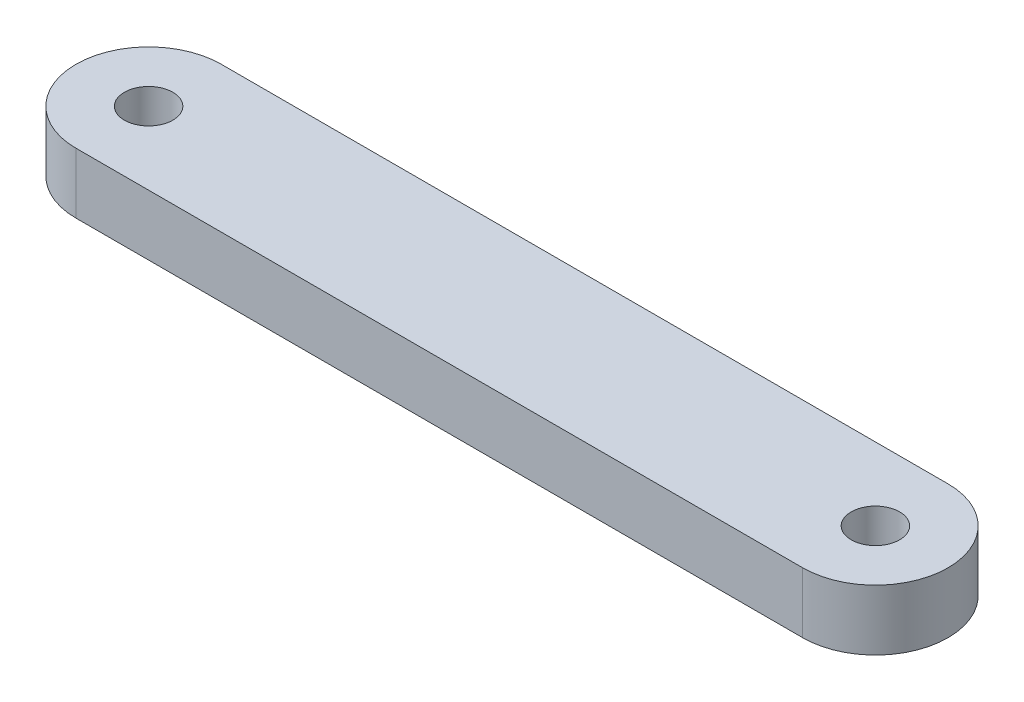
SolidWorks part; units mm, degrees
ref_plane "Front Plane" through (0, 0, 0) normal (0, 0, 1) x (1, 0, 0)
ref_plane "Top Plane" through (0, 0, 0) normal (0, 1, 0) x (1, 0, 0)
ref_plane "Right Plane" through (0, 0, 0) normal (1, 0, 0) x (0, 0, -1)
other "Configuration Table"
sketch "草图1" plane through (0, 0, 0) normal (0, 1, 0) x (1, 0, 0)
  line L0 (-15, 0) -> (15, 0) construction
  line L1 (-15, 3) -> (15, 3)
  line L2 (-15, -3) -> (15, -3)
  arc A0 (-15, 3) -> (-15, -3) centre (-15, 0) ccw
  arc A1 (15, -3) -> (15, 3) centre (15, 0) ccw
  circle A2 centre (-15, 0) radius 1
  circle A3 centre (15, 0) radius 1
  point P2 (0, 0)
  point P12 (15, 0)
  dimension "D3" = 2
  dimension "D1" = 30
  dimension "D2" = 6
extrude "凸台-拉伸1" add sketch "草图1" along normal blind 2.5
sketch "草图2" plane through (0, 2.5, 0) normal (0, 1, 0) x (1, 0, 0)
  line L0 (-11, 3) -> (-11, -3) construction
  line L1 (15, 3) -> (-15, 3) construction
  line L2 (-15, -3) -> (15, -3) construction
  arc A0 (-15, 3) -> (-15, -3) centre (-15, 0) ccw construction
  dimension "D1" = 4
